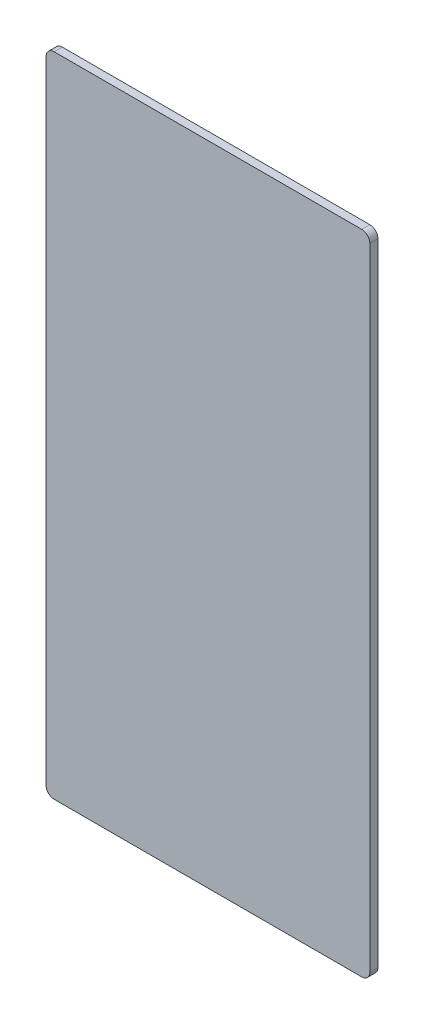
SolidWorks part; units mm, degrees
ref_plane "Front Plane" through (0, 0, 0) normal (0, 0, 1) x (1, 0, 0)
ref_plane "Top Plane" through (0, 0, 0) normal (0, 1, 0) x (1, 0, 0)
ref_plane "Right Plane" through (0, 0, 0) normal (1, 0, 0) x (0, 0, -1)
sketch "Sketch2" plane through (0, 0, 0) normal (0, 0, 1) x (1, 0, 0)
  line L1 (-10, -20) -> (10, -20)
  line L2 (-10, -20) -> (-10, 20)
  line L3 (-10, 20) -> (10, 20)
  line L4 (10, -20) -> (10, 20)
  line L5 (-10, -20) -> (10, 20) construction
  line L6 (-10, 20) -> (10, -20) construction
  point P0 (0, 0)
  dimension "D1" = 40
  dimension "D2" = 20
extrude "Boss-Extrude1" add sketch "Sketch2" along normal blind 0.5
sketch "Sketch4" plane through (0, 0, 0) normal (0, 0, -1) x (-1, 0, 0)
  line L0 (10, 20) -> (10, -20) construction
  line L1 (-9, -19) -> (9, -19)
  line L2 (-9, -19) -> (-9, 19)
  line L3 (-9, 19) -> (9, 19)
  line L4 (9, -19) -> (9, 19)
  line L5 (-9, -19) -> (9, 19) construction
  line L6 (-9, 19) -> (9, -19) construction
  line L8 (10, -20) -> (-10, -20) construction
  point P0 (0, 0)
  dimension "D1" = 1
  dimension "D2" = 1
extrude "Boss-Extrude2" add sketch "Sketch4" along normal blind 0.5
fillet "Fillet1" radius 0.5 4 edges at (10, 20, 0.25) (-10, 20, 0.25) (10, -20, 0.25) (-10, -20, 0.25)
